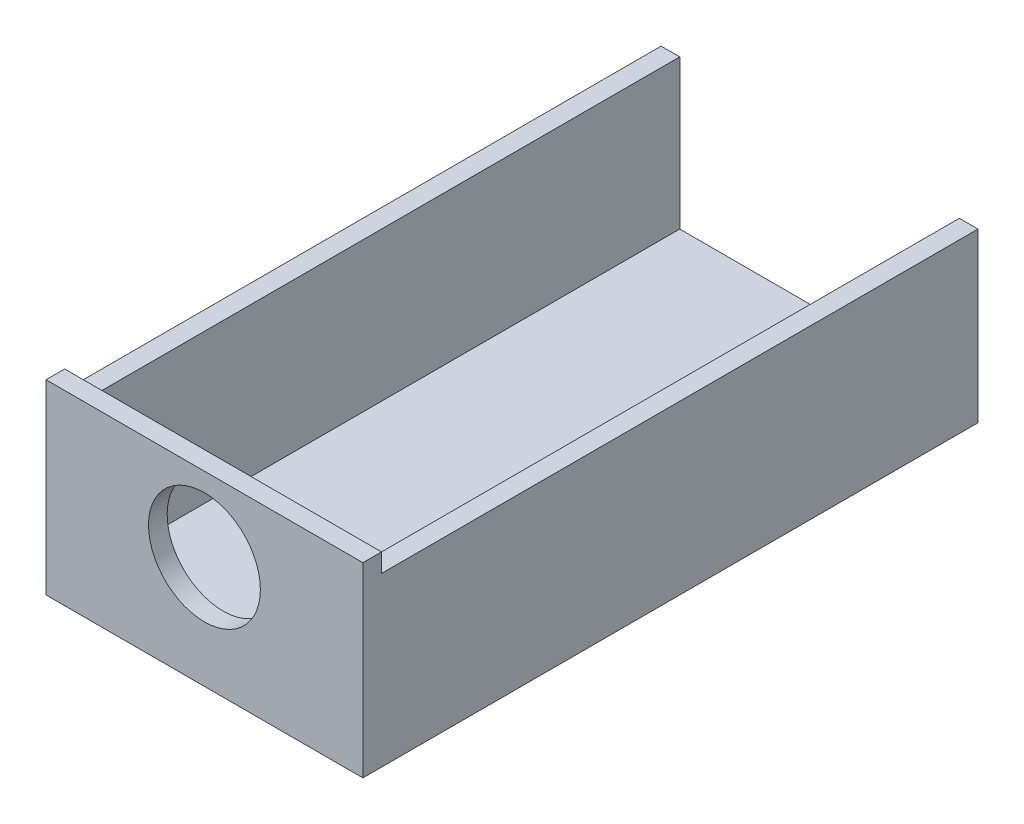
SolidWorks part; units mm, degrees
ref_plane "정면" through (0, 0, 0) normal (0, 0, 1) x (1, 0, 0)
ref_plane "윗면" through (0, 0, 0) normal (0, 1, 0) x (1, 0, 0)
ref_plane "우측면" through (0, 0, 0) normal (1, 0, 0) x (0, 0, -1)
sketch "스케치1" plane through (0, 0, 0) normal (0, 1, 0) x (1, 0, 0)
  line L1 (8.5, -16.5) -> (-8.5, -16.5)
  line L2 (8.5, -16.5) -> (8.5, 16.5)
  line L3 (8.5, 16.5) -> (-8.5, 16.5)
  line L4 (-8.5, -16.5) -> (-8.5, 16.5)
  line L5 (8.5, -16.5) -> (-8.5, 16.5) construction
  line L6 (8.5, 16.5) -> (-8.5, -16.5) construction
  point P0 (0, 0)
  dimension "D1" = 17
  dimension "D2" = 33
extrude "보스-돌출1" add sketch "스케치1" along normal blind 10
sketch "스케치2" plane through (0, 0, 0) normal (0, 1, 0) x (1, 0, 0)
  line L0 (-8.5, 16.5) -> (-8.5, -16.5) construction
  line L1 (-7.5, 16.5) -> (7.5, 16.5)
  line L2 (-7.5, 16.5) -> (-7.5, -15.5)
  line L3 (-7.5, -15.5) -> (7.5, -15.5)
  line L4 (7.5, 16.5) -> (7.5, -15.5)
  line L5 (-8.5, -16.5) -> (8.5, -16.5) construction
  dimension "D1" = 15
  dimension "D2" = 1
  dimension "D3" = 32
  dimension "D4" = 1
extrude "컷-돌출1" cut sketch "스케치2" along normal blind 8 from offset 1
sketch "스케치3" plane through (0, 0, 0) normal (0, 0, 1) x (1, 0, 0)
  line L0 (-8.5, 0) -> (8.5, 0) construction
  circle A0 centre (0, 6) radius 3
  dimension "D1" = 3
  dimension "D2" = 6
extrude "컷-돌출2" cut sketch "스케치3" along normal through all
sketch "스케치5" plane through (0, 0, 0) normal (0, 1, 0) x (1, 0, 0)
  line L0 (8.5, -16.5) -> (8.5, 16.5) construction
  line L1 (-8.5, 16.5) -> (8.5, 16.5)
  line L2 (-8.5, 16.5) -> (-8.5, -15.5)
  line L3 (-8.5, -15.5) -> (8.5, -15.5)
  line L4 (8.5, 16.5) -> (8.5, -15.5)
  line L5 (-8.5, -16.5) -> (8.5, -16.5) construction
  dimension "D1" = 1
extrude "컷-돌출3" cut sketch "스케치5" along normal blind 8 from offset 9
sketch "스케치6" plane through (0, 0, 0) normal (0, 1, 0) x (1, 0, 0)
  line L1 (-8.5, 16.5) -> (8.5, 16.5)
  line L2 (-8.5, 16.5) -> (-8.5, -15.5)
  line L3 (-8.5, -15.5) -> (8.5, -15.5)
  line L4 (8.5, 16.5) -> (8.5, -15.5)
extrude "보스-돌출2" add sketch "스케치6" along normal blind 1 from offset 9 separate body
sketch "스케치7" plane through (0, 10, 0) normal (0, 1, 0) x (1, 0, 0)
  line L4 (-8.5, 16.5) -> (-8.5, -15.5)
  line L5 (-8.5, -15.5) -> (8.5, -15.5)
  line L6 (8.5, -15.5) -> (8.5, 16.5)
  line L7 (8.5, 16.5) -> (-8.5, 16.5)
  line L8 (-8.5, 16.5) -> (-8.5, -15.5)
  line L9 (-8.5, -15.5) -> (8.5, -15.5)
  line L10 (8.5, -15.5) -> (8.5, 16.5)
  line L11 (8.5, 16.5) -> (-8.5, 16.5)
  dimension "D1" = 0
extrude "컷-돌출4" cut sketch "스케치7" against normal blind 1
